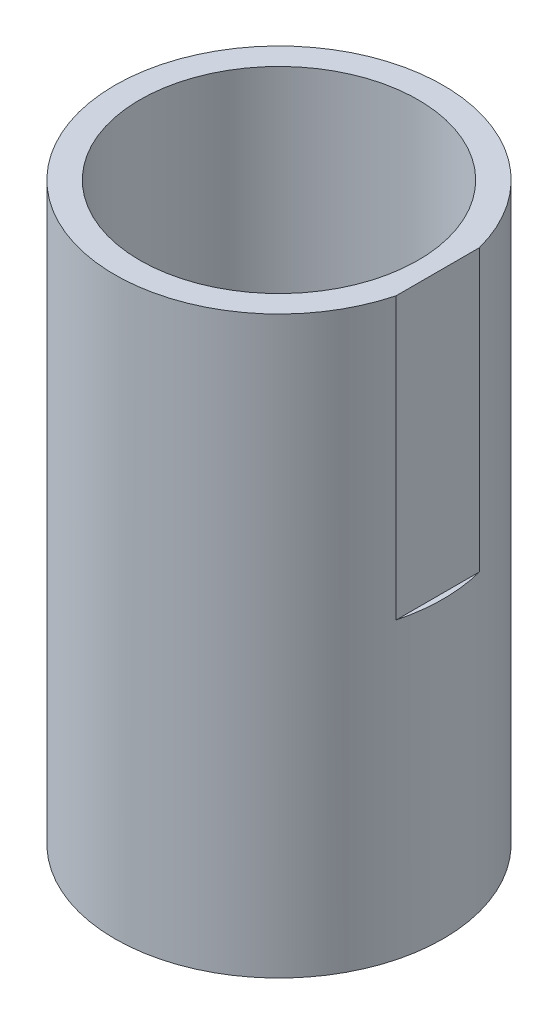
SolidWorks part; units mm, degrees
ref_plane "Front Plane" through (0, 0, 0) normal (0, 0, 1) x (1, 0, 0)
ref_plane "Top Plane" through (0, 0, 0) normal (0, 1, 0) x (1, 0, 0)
ref_plane "Right Plane" through (0, 0, 0) normal (1, 0, 0) x (0, 0, -1)
sketch "Sketch1" plane through (0, 0, 0) normal (0, 1, 0) x (1, 0, 0)
  circle A0 centre (0, 0) radius 24.13
  circle A1 centre (0, 0) radius 20.447
  dimension "D1" = 48.26
  dimension "D2" = 40.894
extrude "Boss-Extrude1" add sketch "Sketch1" along normal mid plane 84.5312
ref_plane "Plane1" through (24.13, 0, 0) normal (1, 0, 0) x (0, 0, -1)
sketch "Sketch2" plane through (24.13, 0, 0) normal (1, 0, 0) x (0, 0, -1)
  line L0 (24.13, 42.2656) -> (-24.13, 42.2656) construction
  line L1 (-6.35, 0.9906) -> (6.35, 0.9906)
  line L2 (-6.35, 0.9906) -> (-6.35, 42.2656)
  line L3 (-6.35, 42.2656) -> (6.35, 42.2656)
  line L4 (6.35, 0.9906) -> (6.35, 42.2656)
  line L5 (-6.35, 0.9906) -> (6.35, 42.2656) construction
  line L6 (-6.35, 42.2656) -> (6.35, 0.9906) construction
  point P0 (0, 21.6281)
  point P7 (0, 0)
  dimension "D1" = 12.7
  dimension "D2" = 41.275
extrude "Cut-Extrude1" cut sketch "Sketch2" against normal blind 0.7874
